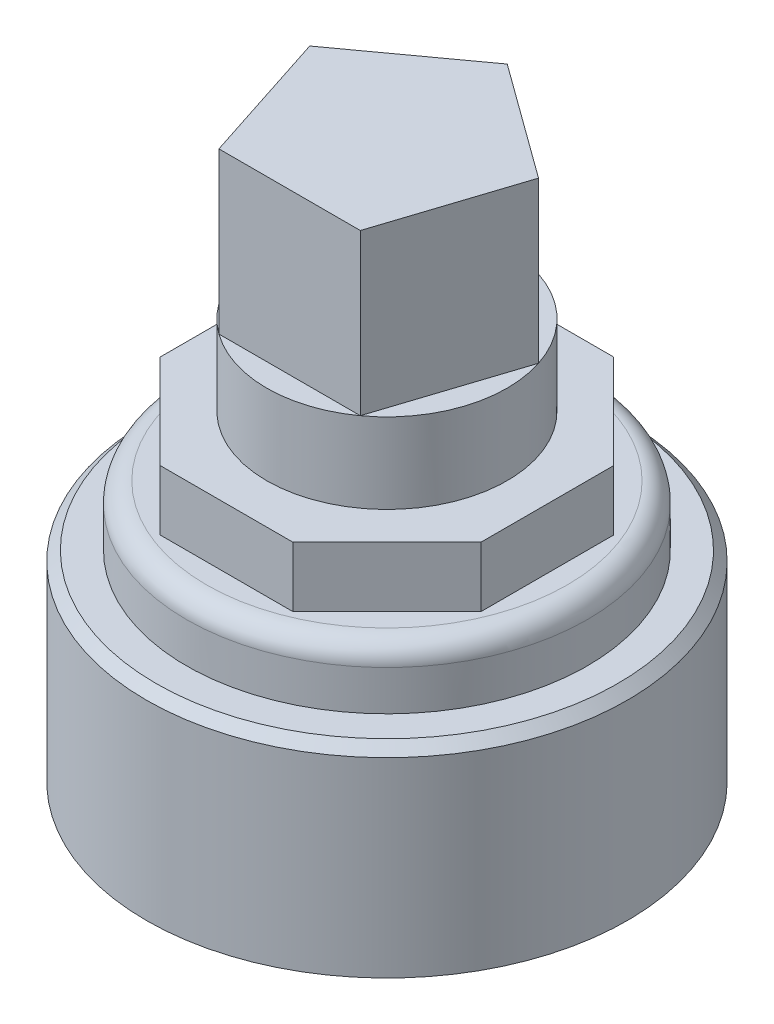
SolidWorks part; units mm, degrees
ref_plane "Front Plane" through (0, 0, 0) normal (0, 0, 1) x (1, 0, 0)
ref_plane "Top Plane" through (0, 0, 0) normal (0, 1, 0) x (1, 0, 0)
ref_plane "Right Plane" through (0, 0, 0) normal (1, 0, 0) x (0, 0, -1)
sketch "Sketch2" plane through (0, 0, 0) normal (0, 1, 0) x (1, 0, 0)
  circle A0 centre (0, 0) radius 38.1
  dimension "D1" = 76.2
extrude "Boss-Extrude1" add sketch "Sketch2" along normal blind 31.75
chamfer "Chamfer1" distance 1.524 angle 45 1 edges at (0, 31.75, 38.1)
sketch "Sketch3" plane through (0, 31.75, 0) normal (0, 1, 0) x (1, 0, 0)
  circle A0 centre (0, 0) radius 31.75
  circle A1 centre (0, 0) radius 36.576
  circle A2 centre (0, 0) radius 36.576
  dimension "D2" = 63.5
  dimension "D1" = 0
extrude "Boss-Extrude3" add sketch "Sketch3" along normal blind 9.525 contours A0
fillet "Fillet1" radius 3.175 1 edges at (0, 41.275, 31.75)
sketch "Sketch4" plane through (0, 41.275, 0) normal (0, 1, 0) x (1, 0, 0)
  line L0 (0, 0) -> (28.575, 0) construction
  line L2 (25.4, 10.521) -> (10.521, 25.4)
  line L3 (10.521, 25.4) -> (-10.521, 25.4)
  line L4 (-10.521, 25.4) -> (-25.4, 10.521)
  line L5 (-25.4, 10.521) -> (-25.4, -10.521)
  line L6 (-25.4, -10.521) -> (-10.521, -25.4)
  line L7 (-10.521, -25.4) -> (10.521, -25.4)
  line L8 (10.521, -25.4) -> (25.4, -10.521)
  line L9 (25.4, -10.521) -> (25.4, 10.521)
  circle A0 centre (0, 0) radius 25.4 construction
  circle A1 centre (0, 0) radius 28.575
  circle A2 centre (0, 0) radius 28.575
  dimension "D2" = 50.8
  dimension "D1" = 0
extrude "Boss-Extrude4" add sketch "Sketch4" along normal blind 9.525 contours L2 L3 L4 L5 L6 L7 L8 L9
sketch "Sketch5" plane through (0, 50.8, 0) normal (0, 1, 0) x (1, 0, 0)
  line L8 (25.4, -10.521) -> (25.4, 10.521)
  line L9 (25.4, 10.521) -> (10.521, 25.4)
  line L10 (10.521, 25.4) -> (-10.521, 25.4)
  line L11 (-10.521, 25.4) -> (-25.4, 10.521)
  line L12 (-25.4, 10.521) -> (-25.4, -10.521)
  line L13 (-25.4, -10.521) -> (-10.521, -25.4)
  line L14 (-10.521, -25.4) -> (10.521, -25.4)
  line L15 (10.521, -25.4) -> (25.4, -10.521)
  line L16 (25.4, -10.521) -> (25.4, 10.521)
  line L17 (25.4, 10.521) -> (10.521, 25.4)
  line L18 (10.521, 25.4) -> (-10.521, 25.4)
  line L19 (-10.521, 25.4) -> (-25.4, 10.521)
  line L20 (-25.4, 10.521) -> (-25.4, -10.521)
  line L21 (-25.4, -10.521) -> (-10.521, -25.4)
  line L22 (-10.521, -25.4) -> (10.521, -25.4)
  line L23 (10.521, -25.4) -> (25.4, -10.521)
  circle A0 centre (0, 0) radius 19.05
  dimension "D2" = 38.1
  dimension "D1" = 0
extrude "Boss-Extrude5" add sketch "Sketch5" along normal blind 12.7 contours A0
sketch "Sketch6" plane through (0, 63.5, 0) normal (0, 1, 0) x (1, 0, 0)
  line L0 (0, 0) -> (19.05, 0) construction
  line L1 (-11.1973, -15.4118) -> (11.1973, -15.4118)
  line L2 (11.1973, -15.4118) -> (18.1176, 5.8868)
  line L3 (18.1176, 5.8868) -> (0, 19.05)
  line L4 (0, 19.05) -> (-18.1176, 5.8868)
  line L5 (-18.1176, 5.8868) -> (-11.1973, -15.4118)
  circle A0 centre (0, 0) radius 15.4118 construction
  circle A1 centre (0, 0) radius 19.05
  circle A2 centre (0, 0) radius 19.05
  dimension "D1" = 0
extrude "Boss-Extrude6" add sketch "Sketch6" along normal blind 25.4 contours L5 L1 L2 L3 L4
